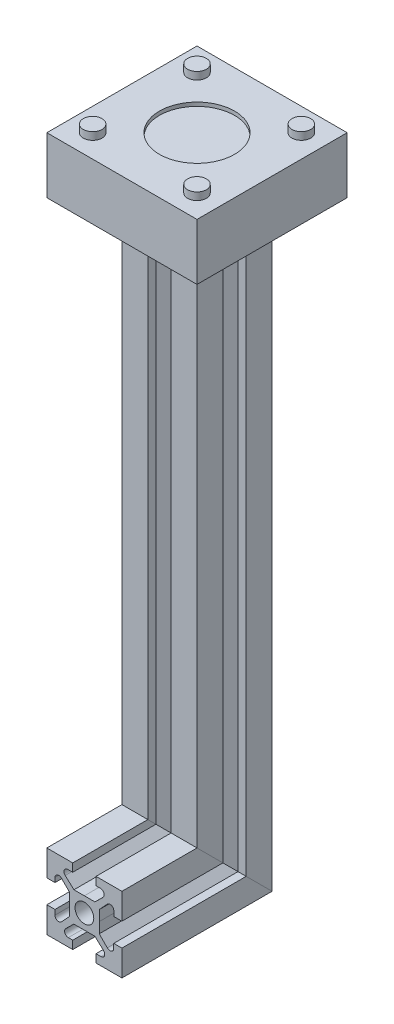
SolidWorks part; units mm, degrees
ref_plane "Front Plane" through (0, 0, 0) normal (0, 0, 1) x (1, 0, 0)
ref_plane "Top Plane" through (0, 0, 0) normal (0, 1, 0) x (1, 0, 0)
ref_plane "Right Plane" through (0, 0, 0) normal (1, 0, 0) x (0, 0, -1)
sketch "Sketch2" plane through (0, 0, 0) normal (0, 0, 1) x (1, 0, 0)
  line L0 (-295.6365, 99.3001) -> (355.6968, 99.3001) construction
  line L1 (53, 177) -> (305, 177) construction
  line L2 (0, 9.9554) -> (0, -10.0446) construction
  line L7 (-10, -10) -> (-3.1, -10)
  line L8 (-10, -10) -> (-10, -3.1)
  line L9 (-10, 10) -> (-3.1, 10)
  line L10 (10, -10) -> (10, -3.1)
  line L11 (-10, -10) -> (10, 10) construction
  line L12 (-10, 10) -> (10, -10) construction
  line L13 (-10, 0) -> (10, 0) construction
  line L14 (-10, 3.1) -> (-7.8186, 3.1)
  line L15 (-7.8186, 3.1) -> (-7.8186, 4.2854)
  line L16 (-6.1072, 4.9882) -> (-3.9647, 2.8197)
  line L17 (-3.9647, 2.8197) -> (-3.9647, 0)
  line L18 (-3.1, 10) -> (-3.1, 7.839)
  line L19 (-3.1, 7.839) -> (-4.4279, 7.839)
  line L20 (-5.1052, 6.1033) -> (-2.7827, 3.9647)
  line L21 (-2.7827, 3.9647) -> (0, 3.9647)
  line L22 (3.1, 10) -> (3.1, 7.8186)
  line L23 (3.1, 7.8186) -> (4.2854, 7.8186)
  line L24 (4.9882, 6.1072) -> (2.8197, 3.9647)
  line L25 (2.8197, 3.9647) -> (0, 3.9647)
  line L26 (6.1033, 5.1052) -> (3.9647, 2.7827)
  line L27 (3.9647, 2.7827) -> (3.9647, 0)
  line L28 (7.839, 3.1) -> (7.839, 4.4279)
  line L29 (10, 3.1) -> (7.839, 3.1)
  line L30 (10, -3.1) -> (7.8186, -3.1)
  line L31 (7.8186, -3.1) -> (7.8186, -4.2854)
  line L32 (6.1072, -4.9882) -> (3.9647, -2.8197)
  line L33 (3.9647, -2.8197) -> (3.9647, 0)
  line L34 (5.1052, -6.1033) -> (2.7827, -3.9647)
  line L35 (2.7827, -3.9647) -> (0, -3.9647)
  line L36 (3.1, -7.839) -> (4.4279, -7.839)
  line L37 (3.1, -10) -> (3.1, -7.839)
  line L38 (-3.1, -10) -> (-3.1, -7.8186)
  line L39 (-3.1, -7.8186) -> (-4.2854, -7.8186)
  line L40 (-4.9882, -6.1072) -> (-2.8197, -3.9647)
  line L41 (-2.8197, -3.9647) -> (0, -3.9647)
  line L42 (-6.1033, -5.1052) -> (-3.9647, -2.7827)
  line L43 (-3.9647, -2.7827) -> (-3.9647, 0)
  line L44 (-7.839, -3.1) -> (-7.839, -4.4279)
  line L45 (-10, -3.1) -> (-7.839, -3.1)
  line L46 (3.1, 10) -> (10, 10)
  line L47 (10, 3.1) -> (10, 10)
  line L48 (3.1, -10) -> (10, -10)
  line L49 (-10, 3.1) -> (-10, 10)
  circle A1 centre (0, 0) radius 2.5
  arc A2 (-4.4279, 7.839) -> (-5.1052, 6.1033) centre (-4.4279, 6.839) ccw
  arc A3 (-7.8186, 4.2854) -> (-6.1072, 4.9882) centre (-6.8186, 4.2854) cw
  arc A4 (4.2854, 7.8186) -> (4.9882, 6.1072) centre (4.2854, 6.8186) cw
  arc A5 (7.839, 4.4279) -> (6.1033, 5.1052) centre (6.839, 4.4279) ccw
  arc A6 (7.8186, -4.2854) -> (6.1072, -4.9882) centre (6.8186, -4.2854) cw
  arc A7 (4.4279, -7.839) -> (5.1052, -6.1033) centre (4.4279, -6.839) ccw
  arc A8 (-4.2854, -7.8186) -> (-4.9882, -6.1072) centre (-4.2854, -6.8186) cw
  arc A9 (-7.839, -4.4279) -> (-6.1033, -5.1052) centre (-6.839, -4.4279) ccw
  dimension "D1" = 3.1
  dimension "D5" = 1
  dimension "D2" = 20
  dimension "D3" = 20
  dimension "D4" = 3.1
  dimension "D6" = 4
sketch "Sketch3" plane through (0, 0, 0) normal (1, 0, 0) x (0, 0, -1)
  line L0 (0, 0) -> (30, 0)
  line L1 (30, 0) -> (30, 150)
sweep "Sweep1" add profiles "Sketch2" path "Sketch3"
sketch "Sketch4" plane through (0, 150, 0) normal (0, 1, 0) x (1, 0, 0)
  line L1 (-20, 10) -> (20, 10)
  line L2 (-20, 10) -> (-20, 50)
  line L3 (-20, 50) -> (20, 50)
  line L4 (20, 10) -> (20, 50)
  line L5 (-20, 10) -> (20, 50) construction
  line L6 (-20, 50) -> (20, 10) construction
  point P0 (0, 30)
extrude "Boss-Extrude1" add sketch "Sketch4" along normal blind 15
sketch "Sketch5" plane through (0, 165, 0) normal (0, 1, 0) x (1, 0, 0)
  line L0 (20, 50) -> (-20, 50) construction
  circle A0 centre (0, 30) radius 10
  dimension "D1" = 20
extrude "Cut-Extrude1" cut sketch "Sketch5" against normal blind 1
sketch "Sketch6" plane through (0, 165, 0) normal (0, 1, 0) x (1, 0, 0)
  line L0 (-20, 50) -> (20, 10) construction
  line L1 (20, 50) -> (-20, 10) construction
  circle A1 centre (-13.8989, 43.8989) radius 2.5
  circle A2 centre (13.8989, 43.8989) radius 2.5
  circle A3 centre (13.8989, 16.1011) radius 2.5
  circle A4 centre (-13.8989, 16.1011) radius 2.5
  point P10 (0, 30)
  dimension "D1" = 4
extrude "Boss-Extrude2" add sketch "Sketch6" along normal blind 2
